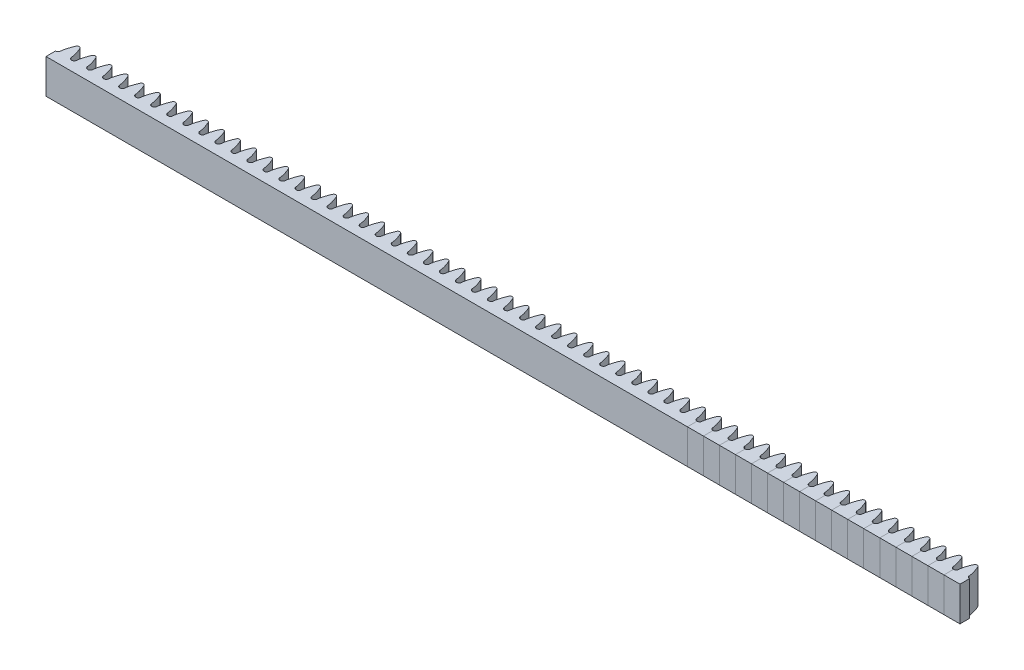
SolidWorks part; units mm, degrees
ref_plane "Front Plane" through (0, 0, 0) normal (0, 0, 1) x (1, 0, 0)
ref_plane "Top Plane" through (0, 0, 0) normal (0, 1, 0) x (1, 0, 0)
ref_plane "Right Plane" through (0, 0, 0) normal (1, 0, 0) x (0, 0, -1)
sketch "Sketch3" plane through (0, 0, 0) normal (0, 1, 0) x (1, 0, 0)
  line L0 (5.3198, 10.3873) -> (5.3198, -8.1) construction
  line L1 (0, -1.75) -> (0, -8.1)
  line L2 (0, 0) -> (159.5929, 0) construction
  line L3 (0, -8.1) -> (5.3198, -8.1)
  line L4 (5.3198, 10.3873) -> (5.3198, -8.1)
  line L5 (0, -1.75) -> (0, 0) construction
  arc A0 (1.7497, -0.0299) -> (0, -1.75) centre (0, 0) cw
  spline S0 degree 4 poles (0, 0) (0.002, 0.1147) (0.0161, 0.3438) (0.061, 0.8006) (0.1903, 1.6665) (0.4314, 2.8191) (0.879, 4.4643) (1.5685, 6.4668) (2.4769, 8.6495) (3.6262, 10.993) (5.2376, 13.865) (7.6021, 17.4816) (11.485, 22.4607) (17.3059, 28.3954) (24.8535, 34.3992) (33.937, 39.9107) (43.6019, 44.3166) (53.696, 47.6168) (64.0854, 49.8114) (74.8615, 50.9224) (85.9113, 50.874) (97.1048, 49.5884) (108.2894, 46.9861) (119.0941, 43.0916) (129.3448, 37.905) (138.4632, 31.6817) (145.5927, 25.2454) (150.9109, 19.0552) (154.6773, 13.4893) (156.8024, 9.4717) (158.0727, 6.3763) (158.7332, 4.3339) (158.9963, 3.4192) (159.2006, 2.6023) (159.3392, 1.9487) (159.4275, 1.4625) (159.4782, 1.1464) (159.5146, 0.8928) (159.5422, 0.6703) (159.5624, 0.4792) (159.5764, 0.3197) (159.5854, 0.192) (159.5913, 0.096) (159.5929, 0.032) (159.5929, 0) knots 0 0 0 0 0 0.002258 0.004516 0.009032 0.017227 0.025422 0.038058 0.050694 0.063734 0.076774 0.102853 0.135674 0.187833 0.239992 0.292151 0.34431 0.396468 0.448627 0.500786 0.557173 0.61356 0.669948 0.726335 0.782722 0.839109 0.8866 0.914793 0.942987 0.971181 0.975864 0.980548 0.985231 0.989914 0.992436 0.993697 0.994957 0.996218 0.997479 0.998109 0.998739 0.99937 1 1 1 1 1 construction
  spline S1 degree 4 poles (0, 0) (0.002, 0.1147) (0.0161, 0.3438) (0.061, 0.8006) (0.1903, 1.6665) (0.4314, 2.8191) (0.879, 4.4643) (1.5685, 6.4668) (2.4769, 8.6495) (3.6262, 10.993) (5.2376, 13.865) (7.6021, 17.4816) (11.485, 22.4607) (17.3059, 28.3954) (24.8535, 34.3992) (33.937, 39.9107) (43.6019, 44.3166) (53.696, 47.6168) (64.0854, 49.8114) (74.8615, 50.9224) (85.9113, 50.874) (97.1048, 49.5884) (108.2894, 46.9861) (119.0941, 43.0916) (129.3448, 37.905) (138.4632, 31.6817) (145.5927, 25.2454) (150.9109, 19.0552) (154.6773, 13.4893) (156.8024, 9.4717) (158.0727, 6.3763) (158.7332, 4.3339) (158.9963, 3.4192) (159.2006, 2.6023) (159.3392, 1.9487) (159.4275, 1.4625) (159.4782, 1.1464) (159.5146, 0.8928) (159.5422, 0.6703) (159.5624, 0.4792) (159.5764, 0.3197) (159.5854, 0.192) (159.5913, 0.096) (159.5929, 0.032) (159.5929, 0) knots 0 0 0 0 0 0.002258 0.004516 0.009032 0.017227 0.025422 0.038058 0.050694 0.063734 0.076774 0.102853 0.135674 0.187833 0.239992 0.292151 0.34431 0.396468 0.448627 0.500786 0.557173 0.61356 0.669948 0.726335 0.782722 0.839109 0.8866 0.914793 0.942987 0.971181 0.975864 0.980548 0.985231 0.989914 0.992436 0.993697 0.994957 0.996218 0.997479 0.998109 0.998739 0.99937 1 1 1 1 1 construction
  spline S2 degree 1 poles (1.7497, -0.0299) (157.8429, 0) knots 0 0 1 1 construction
  spline S3 degree 3 poles (1.7497, -0.0299) (1.7504, 0.0101) (1.7537, 0.0811) (1.7698, 0.2932) (1.8127, 0.6815) (1.9401, 1.4986) (2.2062, 2.6911) (2.6203, 4.123) (3.2761, 6.0189) (4.2613, 8.3515) (6.119, 11.98) (8.885, 16.3042) (12.7517, 21.1294) (17.0662, 25.581) (23.3187, 31.011) (31.9232, 36.8416) (43.1579, 42.2924) (55.0317, 46.1898) (67.3135, 48.5297) (79.7945, 49.31) (92.2756, 48.5302) (104.5575, 46.1908) (116.4314, 42.2939) (127.6663, 36.8436) (136.2713, 31.0133) (142.5238, 25.5837) (146.8388, 21.1323) (150.7056, 16.3073) (153.4718, 11.9836) (155.3301, 8.3546) (156.3151, 6.0229) (156.9717, 4.1262) (157.3169, 2.933) (157.5453, 1.9796) (157.6886, 1.2688) (157.7799, 0.6841) (157.8226, 0.2975) (157.837, 0.1116) (157.8429, 0.0084) (157.8429, 0.007) (157.8429, 0) knots 0 0 0 0 0.000977 0.001953 0.003906 0.007812 0.015625 0.023437 0.031249 0.046874 0.062499 0.093748 0.124998 0.156247 0.187496 0.249995 0.312494 0.374993 0.437491 0.49999 0.562489 0.624988 0.687487 0.749985 0.812484 0.843734 0.874983 0.906232 0.937482 0.953106 0.968731 0.976543 0.984356 0.988262 0.992168 0.996074 0.998027 0.999004 0.999492 0.99998 0.99998 0.99998 0.99998 only from (1.7497, -0.0299) to (5.3198, 10.3873)
  point P8 (5.3198, 10.3873)
  dimension "D2" = 1.75
  dimension "D4" = 90
  dimension "D3" = 5.3198
  dimension "D1" = 1.75
extrude "Boss-Extrude1" add sketch "Sketch3" along normal blind 22.86
mirror "Mirror1" about plane through (5.3198, 22.86, 0) normal (1, 0, 0) of "Boss-Extrude1"
fillet "Fillet1" radius 1.397 1 edges at (5.3198, 11.43, -10.3873)
pattern_linear "LPattern1" count 57 spacing 10.6395 along (1, 0, 0) of bodies 105
sketch "Sketch4" plane through (0, 22.86, 0) normal (0, 1, 0) x (1, 0, 0)
  line L0 (425.5811, -1.75) -> (425.5811, -8.1) construction
  line L1 (0, -8.1) -> (425.5811, -8.1)
  line L2 (0, -8.1) -> (0, -4.925)
  line L3 (0, -4.925) -> (425.5811, -4.925)
  line L4 (425.5811, -8.1) -> (425.5811, -4.925)
extrude "Boss-Extrude2" add sketch "Sketch4" against normal blind 2.54
equation "\"rollerRadius\" = 1.75mm"
equation "\"n\" = 15"
equation "\"R\" = 1"
equation "\"D3@Sketch3\"=\"R\"*pi/\"n\""
equation "\"D1@Sketch3\"=\"rollerRadius\""
equation "\"D3@LPattern1\"=2*pi*\"R\"/\"n\""
